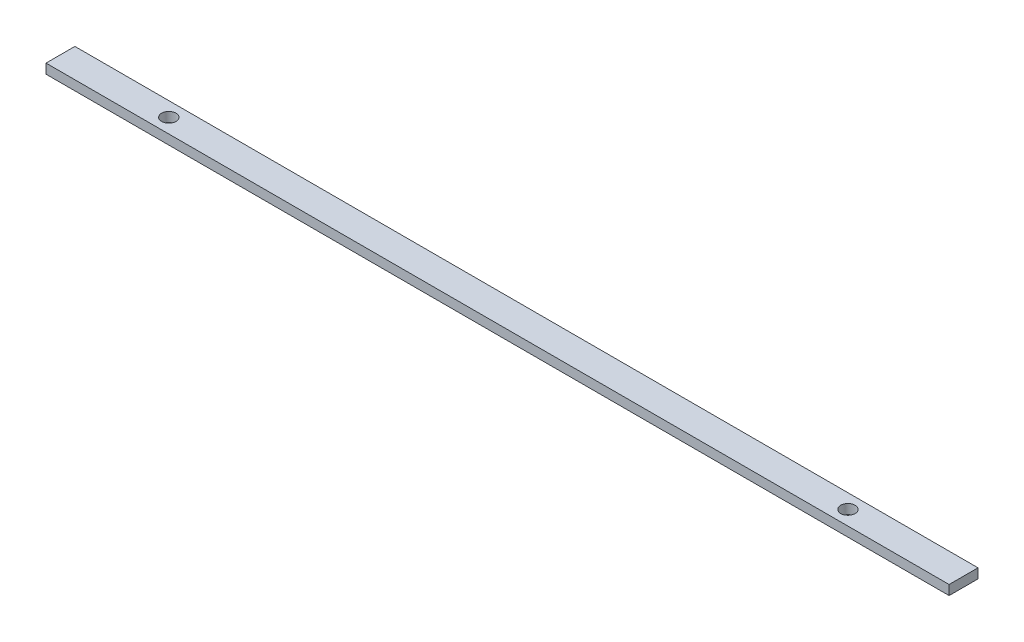
SolidWorks part; units mm, degrees
material "Hexcel AS4C (3000 волосков)"
ref_plane "Front" through (0, 0, 0) normal (0, 0, 1) x (1, 0, 0)
ref_plane "Top" through (0, 0, 0) normal (0, 1, 0) x (1, 0, 0)
ref_plane "Right" through (0, 0, 0) normal (1, 0, 0) x (0, 0, -1)
sketch "Эскиз1" plane through (0, 0, 0) normal (0, 1, 0) x (1, 0, 0)
  line L1 (0, 0) -> (375, 0)
  line L2 (0, 0) -> (0, 12)
  line L3 (0, 12) -> (375, 12)
  line L4 (375, 0) -> (375, 12)
  dimension "D1" = 375
  dimension "D2" = 12
extrude "Бобышка-Вытянуть1" add sketch "Эскиз1" along normal blind 4
sketch "Эскиз2" plane through (0, 4, 0) normal (0, 1, 0) x (1, 0, 0)
  line L0 (0, 0) -> (375, 0) construction
  line L1 (0, 12) -> (0, 0) construction
  circle A0 centre (45, 6) radius 3
  circle A1 centre (327, 6) radius 3
  dimension "D1" = 6
  dimension "D2" = 6
  dimension "D3" = 45
  dimension "D5" = 282
  dimension "D4" = 2
extrude "Вырез-Вытянуть1" cut sketch "Эскиз2" against normal blind 4
